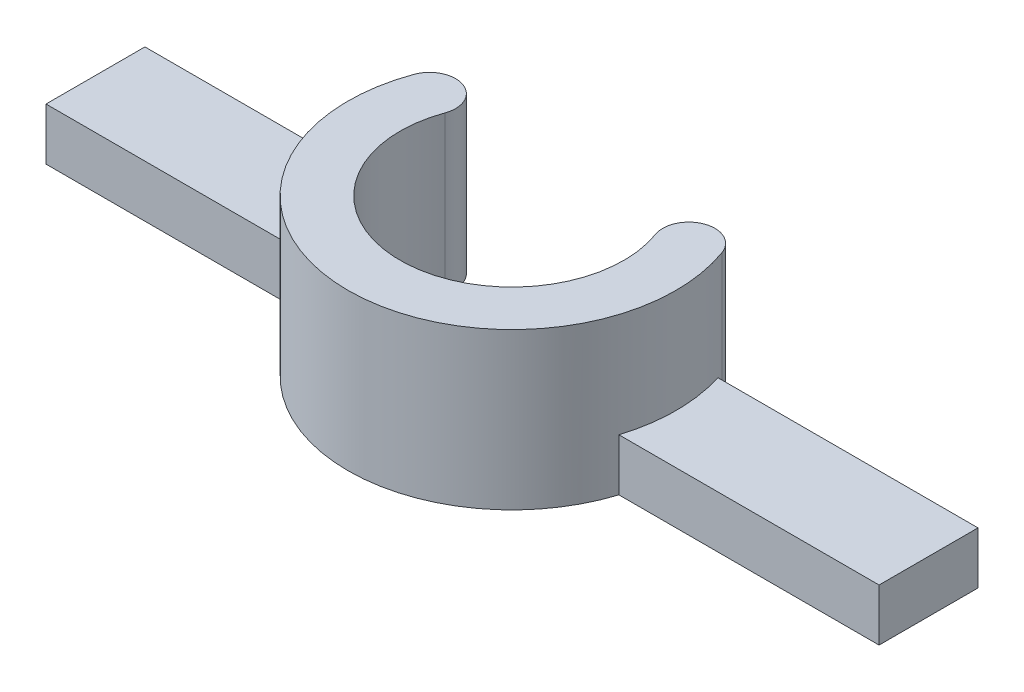
SolidWorks part; units mm, degrees
ref_plane "Front Plane" through (0, 0, 0) normal (0, 0, 1) x (1, 0, 0)
ref_plane "Top Plane" through (0, 0, 0) normal (0, 1, 0) x (1, 0, 0)
ref_plane "Right Plane" through (0, 0, 0) normal (1, 0, 0) x (0, 0, -1)
sketch "Sketch1" plane through (0, 0, 0) normal (0, 1, 0) x (1, 0, 0)
  line L0 (0, 0) -> (6.3, 0)
  line L1 (0, 0) -> (5.9201, 2.1547)
  line L2 (5.9201, 2.1547) -> (4.9804, 1.8127)
  line L3 (0, -55) -> (0, 55) construction
  circle A0 centre (0, 0) radius 4.3
  circle A1 centre (0, 0) radius 6.3
  arc A2 (5.9201, 2.1547) -> (4.0407, 1.4707) centre (4.9804, 1.8127) ccw
  arc A3 (-5.9201, 2.1547) -> (-4.0407, 1.4707) centre (-4.9804, 1.8127) cw
  dimension "D1" = 8.6
  dimension "D2" = 12.6
  dimension "D3" = 20
  dimension "D4" = 1
extrude "Boss-Extrude1" add sketch "Sketch1" along normal blind 6 contours A3 A1 L0 A0 | L0 A1 L1 A0 | L1 A2
sketch "Sketch2" plane through (0, 0, 0) normal (0, 1, 0) x (1, 0, 0)
  line L0 (0, 0) -> (16, 0)
  line L1 (-3.3, 0) -> (3.3, 0) construction
  line L2 (16, 0) -> (16, 1.9)
  line L3 (0, -3.3) -> (0, 3.3) construction
  line L4 (16, 1.9) -> (4.5, 1.9)
  line L5 (16, 1.9) -> (16, -1.9)
  line L6 (16, -1.9) -> (4.5, -1.9)
  line L7 (4.5, 1.9) -> (4.5, -1.9)
  line L8 (-16, -1.9) -> (-4.5, -1.9)
  line L9 (-4.5, 1.9) -> (-4.5, -1.9)
  line L10 (-16, 1.9) -> (-4.5, 1.9)
  line L11 (-16, 1.9) -> (-16, -1.9)
  dimension "D1" = 16
  dimension "D2" = 1.9
  dimension "D3" = 3.8
  dimension "D4" = 11.5
extrude "Boss-Extrude2" add sketch "Sketch2" along normal blind 2 contours L10 L11 L8 L9 | L0 L7 L6 L5 | L4 L7 L0 L2
